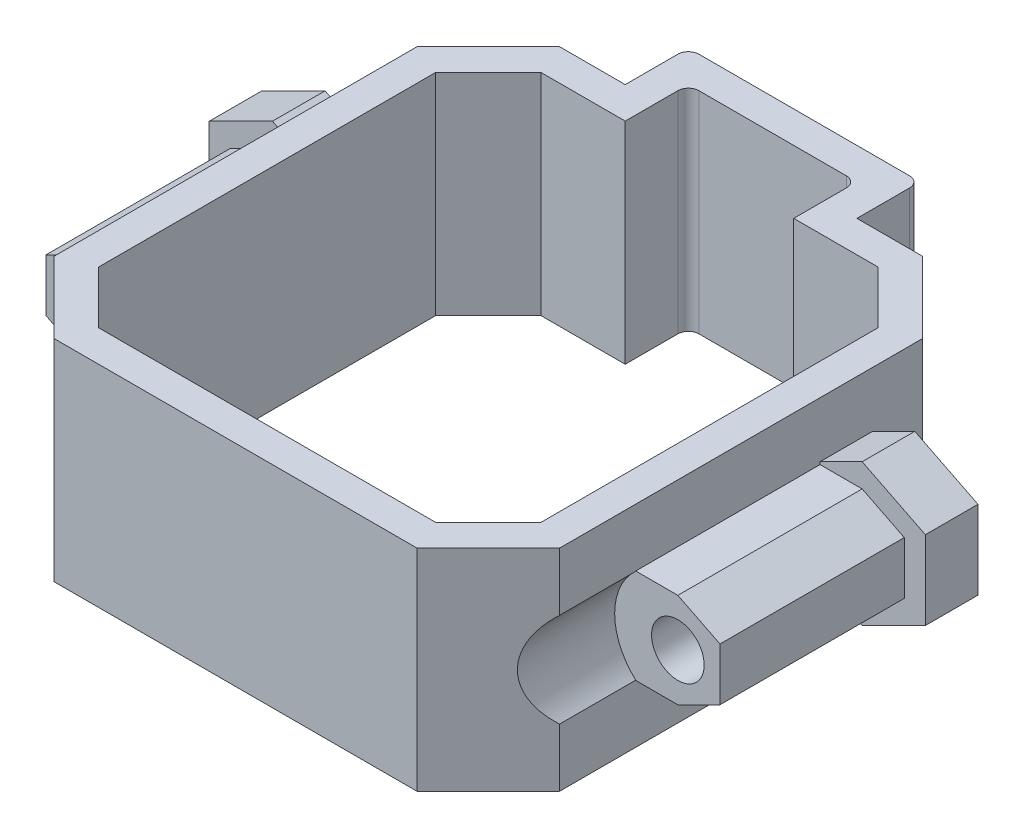
SolidWorks part; units mm, degrees
ref_plane "Plano frontal" through (0, 0, 0) normal (0, 0, 1) x (1, 0, 0)
ref_plane "Plano superior" through (0, 0, 0) normal (0, 1, 0) x (1, 0, 0)
ref_plane "Plano direito" through (0, 0, 0) normal (1, 0, 0) x (0, 0, -1)
sketch "Esboço1" plane through (0, 0, 0) normal (0, 1, 0) x (1, 0, 0)
  line L8 (0, -24) -> (0, 24)
  line L18 (0, 21) -> (16, 21)
  line L19 (21, 16) -> (21, 0)
  line L20 (24, 0) -> (-24, 0)
  line L21 (11, 24) -> (17.2426, 24)
  line L25 (16, 21) -> (21, 16)
  line L26 (17.2426, 24) -> (24, 17.2426)
  line L27 (24, 17.2426) -> (24, 0)
  line L29 (-17.2426, 24) -> (-24, 17.2426)
  line L30 (-24, 17.2426) -> (-24, -17.2426)
  line L31 (-21, 16) -> (-21, -16)
  line L32 (-16, 21) -> (-21, 16)
  line L33 (0, 21) -> (-16, 21)
  line L34 (0, -21) -> (-16, -21)
  line L35 (-16, -21) -> (-21, -16)
  line L36 (-17.2426, -24) -> (-24, -17.2426)
  line L37 (0, -24) -> (-17.2426, -24)
  line L38 (24, -17.2426) -> (24, 0)
  line L39 (17.2426, -24) -> (24, -17.2426)
  line L40 (16, -21) -> (21, -16)
  line L41 (0, -24) -> (17.2426, -24)
  line L42 (21, -16) -> (21, 0)
  line L43 (0, -21) -> (16, -21)
  line L44 (0, 21) -> (0, 27)
  line L45 (0, 27) -> (7, 27)
  line L46 (8, 26) -> (8, 21)
  line L47 (0, 30) -> (10, 30)
  line L48 (11, 29) -> (11, 24)
  line L49 (-8, 26) -> (-8, 21)
  line L50 (0, 27) -> (-7, 27)
  line L51 (-11, 29) -> (-11, 24)
  line L52 (0, 30) -> (-10, 30)
  line L53 (8, 27) -> (8, 24) construction
  line L54 (-11, 24) -> (-17.2426, 24)
  line L55 (0, 27) -> (8, 27) construction
  line L56 (0, 24) -> (17.2426, 24) construction
  line L57 (0, 30) -> (11, 30) construction
  line L58 (11, 30) -> (11, 24) construction
  arc A1 (-7, 27) -> (-8, 26) centre (-7, 26) ccw
  arc A2 (7, 27) -> (8, 26) centre (7, 26) cw
  arc A3 (10, 30) -> (11, 29) centre (10, 29) cw
  arc A4 (-10, 30) -> (-11, 29) centre (-10, 29) ccw
  point P1 (0, 0)
  point P5 (0, 26)
  point P6 (26, 26)
  point P13 (-21, 0)
  point P21 (-21, 0)
  point P43 (-8, 27)
  point P50 (11, 30)
  point P53 (-11, 30)
  dimension "D2" = 3
  dimension "D3" = 1
  dimension "D1" = 3
extrude "Ressalto-extrusão1" add sketch "Esboço1" along normal mid plane 20 contours L52 A4 L51 L54 L29 L30 L20 L31 L32 L33 L49 A1 L50 L45 A2 L46 L18 L25 L19 L27 L26 L21 L48 A3 L47 | L43 L8 L41 L39 L38 L20 L42 L40 | L37 L8 L34 L35 L31 L20 L30 L36
sketch "Esboço2" plane through (0, 0, 0) normal (0, 0, 1) x (1, 0, 0)
  line L0 (0, 0) -> (24, 0)
  line L1 (24, 10) -> (24, -10) construction
  line L2 (24, 0) -> (32, 0)
  line L3 (28, 0) -> (28, 4.5)
  line L4 (32, -2.5) -> (32, 2.5)
  line L5 (32, 2.5) -> (28, 4.5)
  line L6 (28, 4.5) -> (24, 4.5)
  line L7 (32, -2.5) -> (28, -4.5)
  line L8 (28, -4.5) -> (24, -4.5)
  line L9 (24, 4.5) -> (24, -4.5)
  line L10 (0, 0) -> (0, 10)
  line L11 (-17.2426, 10) -> (17.2426, 10) construction
  line L12 (-24, 4.5) -> (-24, -4.5)
  line L13 (-28, -4.5) -> (-24, -4.5)
  line L14 (-32, -2.5) -> (-28, -4.5)
  line L15 (-28, 4.5) -> (-24, 4.5)
  line L16 (-32, 2.5) -> (-28, 4.5)
  line L17 (-32, -2.5) -> (-32, 2.5)
  line L18 (-28, 0) -> (-28, 4.5)
  line L19 (-24, 0) -> (-32, 0)
  circle A0 centre (28, 0) radius 2.5
  circle A1 centre (-28, 0) radius 2.5
extrude "Ressalto-extrusão2" add sketch "Esboço2" against normal mid plane 20 contours L18 A1 L19 L12 L15 | L19 A1 L18 L16 L17 | L19 A1 L17 L14 L13 L12 | A0 L2 L9 L8 L7 L4 | A0 L3 L6 L9 L2 | A0 L2 L4 L5 L3
sketch "Esboço3" plane through (0, 0, 0) normal (0, 1, 0) x (1, 0, 0)
  line L0 (0, 0) -> (40, 0)
  line L1 (40, -40) -> (40, 40)
  line L2 (40, 40) -> (-40, 40)
  line L3 (-40, 40) -> (-40, -40)
  line L4 (-40, 0) -> (0, 0)
  line L5 (40, -40) -> (-40, -40)
sketch "Esboço4" plane through (0, 0, 10) normal (0, 0, 1) x (1, 0, 0)
  line L0 (-32, -2.5) -> (-32, 2.5)
  line L1 (-32, 2.5) -> (-28, 4.5)
  line L2 (-28, 4.5) -> (-24, 4.5)
  line L3 (-24, 4.5) -> (-24, -4.5)
  line L4 (-24, -4.5) -> (-28, -4.5)
  line L5 (-28, -4.5) -> (-32, -2.5)
  line L6 (0, 0) -> (0, 10)
  line L7 (-17.2426, 10) -> (17.2426, 10) construction
  line L8 (40, 0) -> (-40, 0) construction
  circle A0 centre (-28, 0) radius 2.5
  circle A1 centre (-28, 0) radius 6
  circle A2 centre (28, 0) radius 2.5
  circle A3 centre (28, 0) radius 6
extrude "Corte-extrusão1" cut sketch "Esboço4" along normal blind 21 contours L3 A1 | A3 A2 | A2
sketch "Esboço5" plane through (0, 0, -10) normal (0, 0, -1) x (-1, 0, 0)
  line L0 (-32, 2.5) -> (-32, -2.5)
  line L1 (-32, -2.5) -> (-28, -4.5)
  line L3 (-24, -2.5) -> (-24, 2.5)
  line L5 (-32, 2.5) -> (-28, 4.5) construction
  line L6 (-28, 4.5) -> (-32, 2.5)
  line L7 (-28, 4.5) -> (-24, 2.5)
  line L8 (-28, -4.5) -> (-24, -2.5)
  line L9 (-28, 6.7361) -> (-22, 3.7361)
  line L10 (-22, -3.7361) -> (-22, 3.7361)
  line L11 (-28, -6.7361) -> (-22, -3.7361)
  line L12 (-34, -3.7361) -> (-28, -6.7361)
  line L13 (-34, 3.7361) -> (-34, -3.7361)
  line L14 (-28, 6.7361) -> (-34, 3.7361)
  line L15 (0, 0) -> (0, 5.5027)
  line L16 (28, 6.7361) -> (34, 3.7361)
  line L17 (34, 3.7361) -> (34, -3.7361)
  line L18 (34, -3.7361) -> (28, -6.7361)
  line L19 (28, -6.7361) -> (22, -3.7361)
  line L20 (22, -3.7361) -> (22, 3.7361)
  line L21 (28, 6.7361) -> (22, 3.7361)
  line L22 (28, -4.5) -> (24, -2.5)
  line L23 (28, 4.5) -> (24, 2.5)
  line L24 (28, 4.5) -> (32, 2.5)
  line L25 (24, -2.5) -> (24, 2.5)
  line L26 (32, -2.5) -> (28, -4.5)
  line L27 (32, 2.5) -> (32, -2.5)
  line M9 (-28, 4.5) -> (-32, 2.5)
  line M10 (-32, 2.5) -> (-32, -2.5)
  line M11 (-32, -2.5) -> (-28, -4.5)
  line M12 (-28, -4.5) -> (-24, -4.5)
  line M13 (-24, -4.5) -> (-24, 4.5)
  line M14 (-24, 4.5) -> (-28, 4.5)
  dimension "D1" = 2
extrude "Ressalto-extrusão3" add sketch "Esboço5" along normal mid plane 5 contours L9 L14 L13 L12 L11 L10 M9 M14 M13 M12 M11 M10 | L7 M14 M13 | L8 M12 M13 | L16 L21 L20 L19 L18 L17 L24 L27 L26 L22 L25 L23
